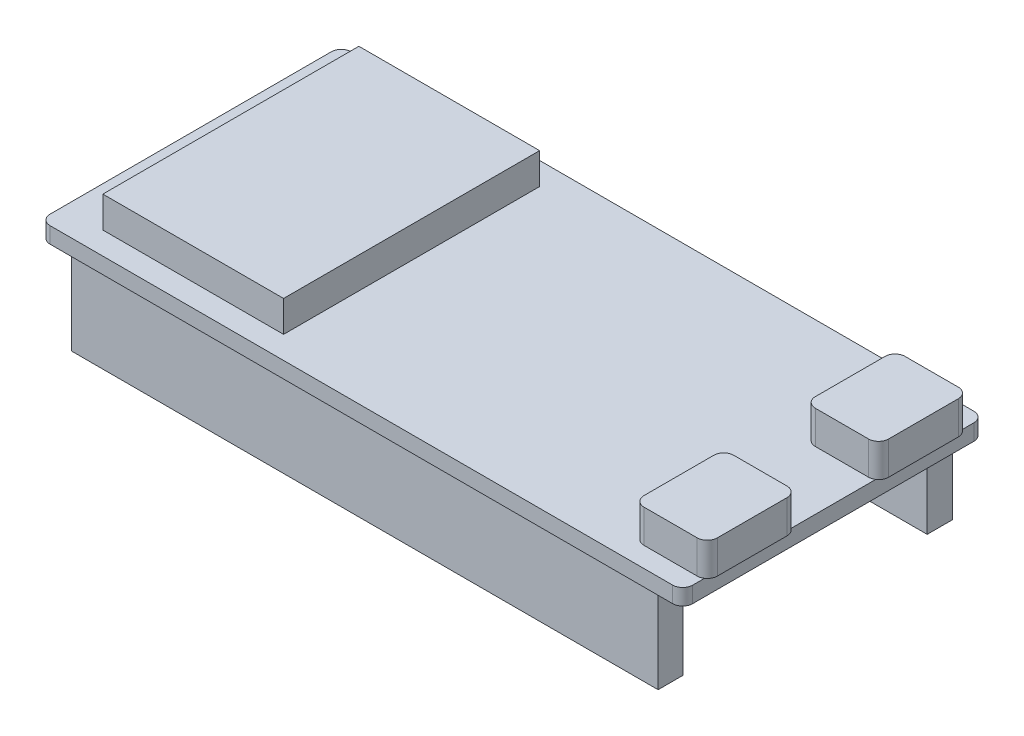
SolidWorks part; units mm, degrees
ref_plane "Front Plane" through (0, 0, 0) normal (0, 0, 1) x (1, 0, 0)
ref_plane "Top Plane" through (0, 0, 0) normal (0, 1, 0) x (1, 0, 0)
ref_plane "Right Plane" through (0, 0, 0) normal (1, 0, 0) x (0, 0, -1)
sketch "Sketch1" plane through (0, 0, 0) normal (0, 1, 0) x (1, 0, 0)
  line L0 (-18, -20) -> (44, -20)
  line L1 (45, -21) -> (45, -49)
  line L2 (44, -50) -> (-18, -50)
  line L3 (-19, -49) -> (-19, -21)
  arc A0 (-19, -21) -> (-18, -20) centre (-18, -21) cw
  arc A1 (44, -20) -> (45, -21) centre (44, -21) cw
  arc A2 (45, -49) -> (44, -50) centre (44, -49) cw
  arc A3 (-18, -50) -> (-19, -49) centre (-18, -49) cw
extrude "Board" add sketch "Sketch1" along normal blind 1.6 from offset 12.5
sketch "Sketch2" plane through (0, 0, 0) normal (0, 1, 0) x (1, 0, 0)
  line L0 (-15, -22.25) -> (3, -22.25)
  line L1 (3, -22.25) -> (3, -47.75)
  line L2 (3, -47.75) -> (-15, -47.75)
  line L3 (-15, -47.75) -> (-15, -22.25)
extrude "WROOM" add sketch "Sketch2" along normal blind 3.1 from offset 14.1
sketch "Sketch3" plane through (0, 0, 0) normal (0, 1, 0) x (1, 0, 0)
  line L0 (39.15, -22) -> (44.45, -22)
  line L1 (45.45, -23) -> (45.45, -29.94)
  line L2 (44.45, -30.94) -> (39.15, -30.94)
  line L3 (38.15, -29.94) -> (38.15, -23)
  line L4 (39.15, -39.06) -> (44.45, -39.06)
  line L5 (45.45, -40.06) -> (45.45, -47)
  line L6 (44.45, -48) -> (39.15, -48)
  line L7 (38.15, -47) -> (38.15, -40.06)
  arc A0 (38.15, -23) -> (39.15, -22) centre (39.15, -23) cw
  arc A1 (44.45, -22) -> (45.45, -23) centre (44.45, -23) cw
  arc A2 (45.45, -29.94) -> (44.45, -30.94) centre (44.45, -29.94) cw
  arc A3 (39.15, -30.94) -> (38.15, -29.94) centre (39.15, -29.94) cw
  arc A4 (38.15, -40.06) -> (39.15, -39.06) centre (39.15, -40.06) cw
  arc A5 (44.45, -39.06) -> (45.45, -40.06) centre (44.45, -40.06) cw
  arc A6 (45.45, -47) -> (44.45, -48) centre (44.45, -47) cw
  arc A7 (39.15, -48) -> (38.15, -47) centre (39.15, -47) cw
extrude "USB-C" add sketch "Sketch3" along normal blind 3.3 from offset 14.1
sketch "Sketch4" plane through (0, 0, 0) normal (0, 1, 0) x (1, 0, 0)
  line L0 (-16.2, -20.35) -> (42.2, -20.35)
  line L1 (42.2, -20.35) -> (42.2, -22.85)
  line L2 (42.2, -22.85) -> (-16.2, -22.85)
  line L3 (-16.2, -22.85) -> (-16.2, -20.35)
  line L4 (-16.2, -47.15) -> (42.2, -47.15)
  line L5 (42.2, -47.15) -> (42.2, -49.65)
  line L6 (42.2, -49.65) -> (-16.2, -49.65)
  line L7 (-16.2, -49.65) -> (-16.2, -47.15)
extrude "Headers" add sketch "Sketch4" along normal blind 8.5 from offset 4
